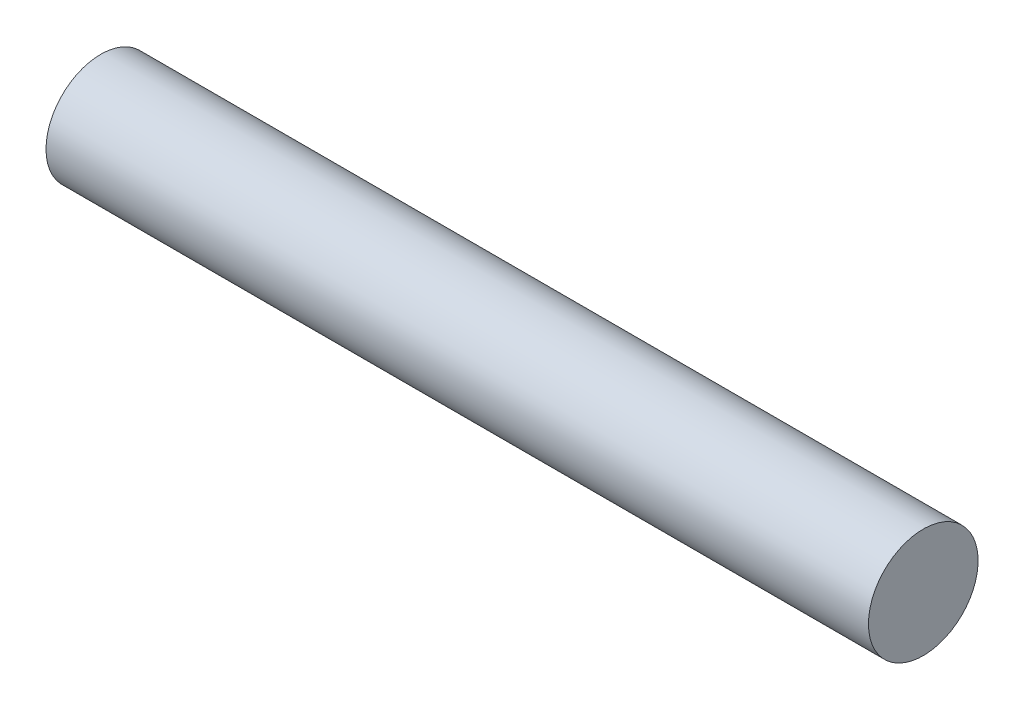
SolidWorks part; units mm, degrees
ref_plane "Front Plane" through (0, 0, 0) normal (0, 0, 1) x (1, 0, 0)
ref_plane "Top Plane" through (0, 0, 0) normal (0, 1, 0) x (1, 0, 0)
ref_plane "Right Plane" through (0, 0, 0) normal (1, 0, 0) x (0, 0, -1)
sketch "Sketch1" plane through (0, 0, 0) normal (0, 0, 1) x (1, 0, 0)
  line L0 (-27.0684, 0) -> (28.7984, 0) construction
  line L1 (57.15, 7.62) -> (-57.15, 7.62)
  line L2 (-57.15, 7.62) -> (-57.15, 0)
  line L3 (57.15, 7.62) -> (57.15, 0)
  line L4 (57.15, 0) -> (-57.15, 0)
  point P6 (0, 7.62)
  point P8 (0, 13.7377)
  point P9 (-44.3271, 0)
  point P10 (44.681, 0)
  point P11 (0, 0)
  point P12 (0, 2.4837)
  point P13 (0, 7.605)
  point P14 (25.4, 0)
  point P15 (0, 7.62)
  point P16 (0, 0)
  point P17 (0, 0)
  point P18 (0, 0)
  point P19 (0, 7.62)
  point P20 (0, 7.62)
  dimension "D1" = 114.3
  dimension "D2" = 7.62
  dimension "D3" = 7.62
revolve "Revolve10" add sketch "Sketch1" angle 360 about L0
